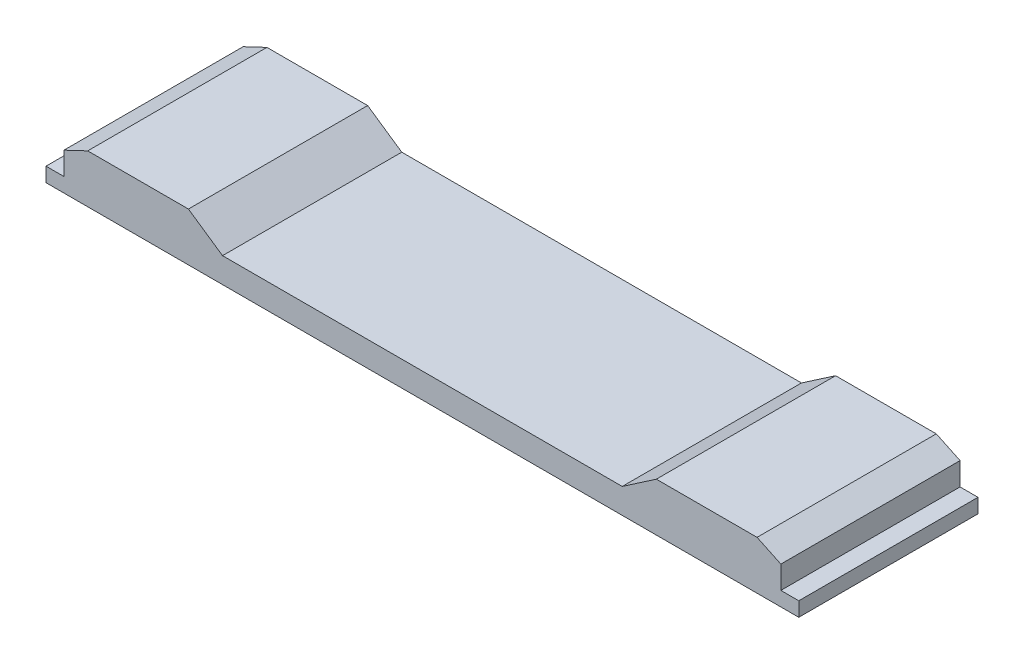
SolidWorks part; units mm, degrees
ref_plane "Спереди" through (0, 0, 0) normal (0, 0, 1) x (1, 0, 0)
ref_plane "Сверху" through (0, 0, 0) normal (0, 1, 0) x (1, 0, 0)
ref_plane "Справа" through (0, 0, 0) normal (1, 0, 0) x (0, 0, -1)
sketch "Эскиз1" plane through (0, 0, 0) normal (0, 0, 1) x (1, 0, 0)
  line L0 (0, 27.73) -> (0, 26.33) construction
  line L1 (20, 26.33) -> (21, 26.33)
  line L2 (-20, 27.13) -> (-20, 28.403)
  line L3 (20, 27.13) -> (21, 27.13)
  line L4 (21, 26.33) -> (21, 27.13)
  line L5 (-21, 26.33) -> (-21, 27.13)
  line L6 (-20, 27.13) -> (-21, 27.13)
  line L7 (-20, 26.33) -> (-21, 26.33)
  line L8 (-20, 28.403) -> (-18.6735, 29.032)
  line L9 (-18.6735, 29.032) -> (-13.0537, 29.032)
  line L10 (-13.0537, 29.032) -> (-11.1508, 27.73)
  line L11 (-11.1508, 27.73) -> (11.1508, 27.73)
  line L12 (11.1508, 27.73) -> (13.0537, 29.032)
  line L13 (13.0537, 29.032) -> (18.6735, 29.032)
  line L14 (18.6735, 29.032) -> (20, 28.403)
  line L15 (-11.1508, 27.73) -> (-13.0537, 29.032) construction
  line L16 (-18.6735, 29.032) -> (-20.3, 28.2607) construction
  line L17 (20.3, 28.2607) -> (18.6735, 29.032) construction
  line L28 (-20, 26.33) -> (20, 26.33)
  line L31 (20, 27.13) -> (20, 28.403)
  point P1 (0, 26.33)
  point P9 (0, 0)
  point P10 (-11.1508, 27.73)
  point P17 (-13.0537, 29.032)
  point P20 (-18.7508, 28.9954)
  point P23 (0, 0)
  point P24 (13.0537, 29.032)
  point P25 (0, 0)
  point P26 (20, 28.403)
  point P33 (0, 51.6036)
  dimension "D3" = 0.8
  dimension "D1" = 40
  dimension "D2" = 1.4
  dimension "D4" = 1
extrude "Бобышка-Вытянуть1" add sketch "Эскиз1" along normal blind 10
